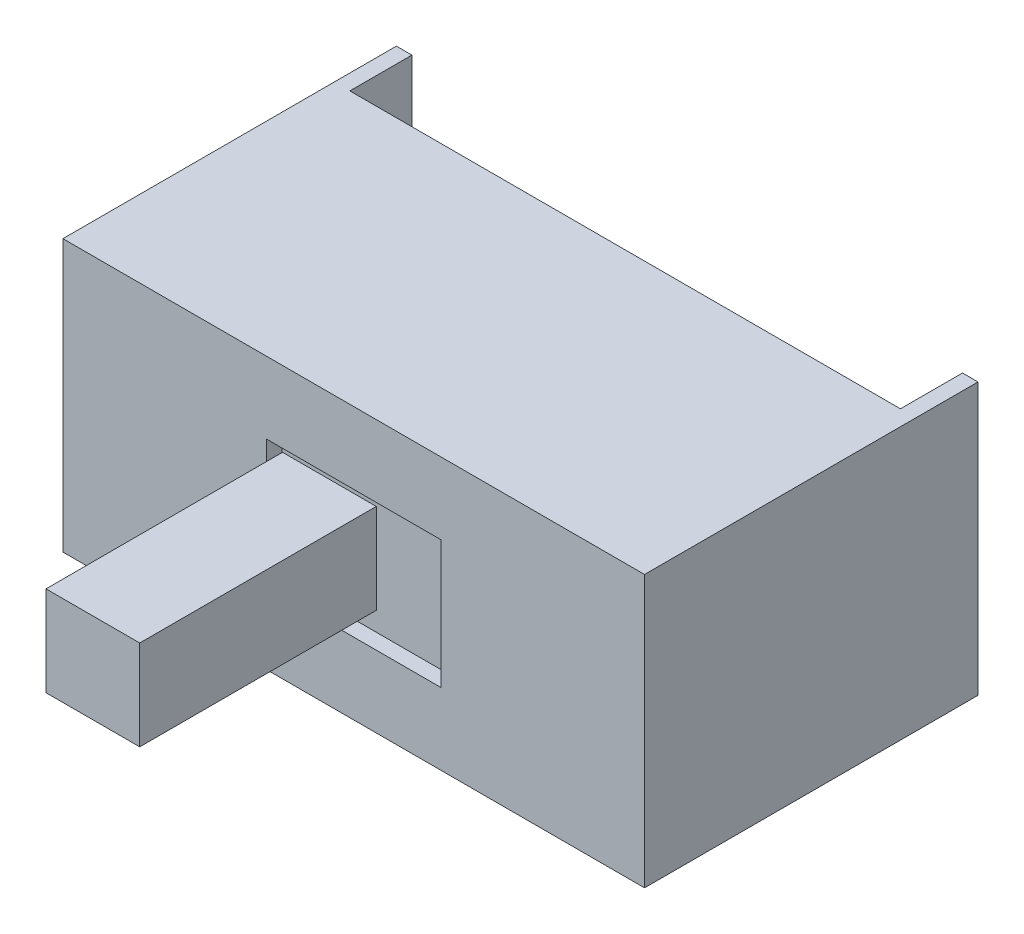
SolidWorks part; units mm, degrees
ref_plane "Спереди" through (0, 0, 0) normal (0, 0, 1) x (1, 0, 0)
ref_plane "Сверху" through (0, 0, 0) normal (0, 1, 0) x (1, 0, 0)
ref_plane "Справа" through (0, 0, 0) normal (1, 0, 0) x (0, 0, -1)
sketch "Эскиз1" plane through (0, 0, 0) normal (0, 0, 1) x (1, 0, 0)
  line L0 (0, 3.5) -> (15, 3.5) construction
  line L1 (0, 0) -> (15, 0)
  line L2 (0, 0) -> (0, 7)
  line L3 (0, 7) -> (15, 7)
  line L4 (15, 0) -> (15, 7)
  line L5 (9.75, 5.15) -> (5.25, 5.15)
  line L6 (9.75, 5.15) -> (9.75, 1.85)
  line L7 (9.75, 1.85) -> (5.25, 1.85)
  line L8 (5.25, 5.15) -> (5.25, 1.85)
  line L9 (9.75, 3.5) -> (5.25, 3.5) construction
  line L10 (7.5, 7) -> (7.5, 0) construction
  line L11 (7.5, 5.15) -> (7.5, 1.85) construction
  dimension "D1" = 15
  dimension "D2" = 7
  dimension "D3" = 4.5
  dimension "D4" = 3.3
extrude "Бобышка-Вытянуть1" add sketch "Эскиз1" along normal blind 0.4
sketch "Эскиз2" plane through (0, 0, 0) normal (0, 0, -1) x (-1, 0, 0)
  line L0 (-5.3789, 3.5) -> (-7.8789, 3.5) construction
  line L1 (-15, 7) -> (0, 7)
  line L2 (-15, 7) -> (-15, 0)
  line L3 (-15, 0) -> (0, 0)
  line L4 (0, 7) -> (0, 0)
  line L9 (-5.25, 3.5) -> (-9.75, 3.5) construction
  line L10 (-5.25, 5.15) -> (-5.25, 1.85) construction
  line L11 (-9.75, 1.85) -> (-9.75, 5.15) construction
extrude "Бобышка-Вытянуть2" add sketch "Эскиз2" along normal blind 6.6
sketch "Эскиз3" plane through (15, 0, 0) normal (1, 0, 0) x (0, 0, -1)
  line L1 (-0.4, 7) -> (8.2, 7)
  line L2 (-0.4, 7) -> (-0.4, 0)
  line L3 (-0.4, 0) -> (8.2, 0)
  line L4 (8.2, 7) -> (8.2, 0)
  dimension "D1" = 8.6
extrude "Бобышка-Вытянуть3" add sketch "Эскиз3" against normal blind 0.4 contours L1 L4 L3 L2
sketch "Эскиз4" plane through (0, 0, 0) normal (-1, 0, 0) x (0, 0, 1)
  line L1 (0.4, 7) -> (-8.2, 7)
  line L2 (0.4, 7) -> (0.4, 0)
  line L3 (0.4, 0) -> (-8.2, 0)
  line L4 (-8.2, 7) -> (-8.2, 0)
  dimension "D1" = 8.6
extrude "Бобышка-Вытянуть4" add sketch "Эскиз4" against normal blind 0.4 contours L4 L3 L2 L1
sketch "Эскиз5" plane through (0, 0, 0) normal (0, 0, 1) x (1, 0, 0)
  line L0 (7.6812, 3.5) -> (5.2638, 3.5) construction
  line L1 (5.2638, 4.6602) -> (7.6812, 4.6602)
  line L2 (5.2638, 4.6602) -> (5.2638, 2.3398)
  line L3 (5.2638, 2.3398) -> (7.6812, 2.3398)
  line L4 (7.6812, 4.6602) -> (7.6812, 2.3398)
  line L5 (9.75, 3.5) -> (5.25, 3.5) construction
  line L7 (9.75, 1.85) -> (9.75, 5.15) construction
  line L8 (5.25, 5.15) -> (5.25, 1.85) construction
extrude "Бобышка-Вытянуть5" add sketch "Эскиз5" along normal blind 6.1
